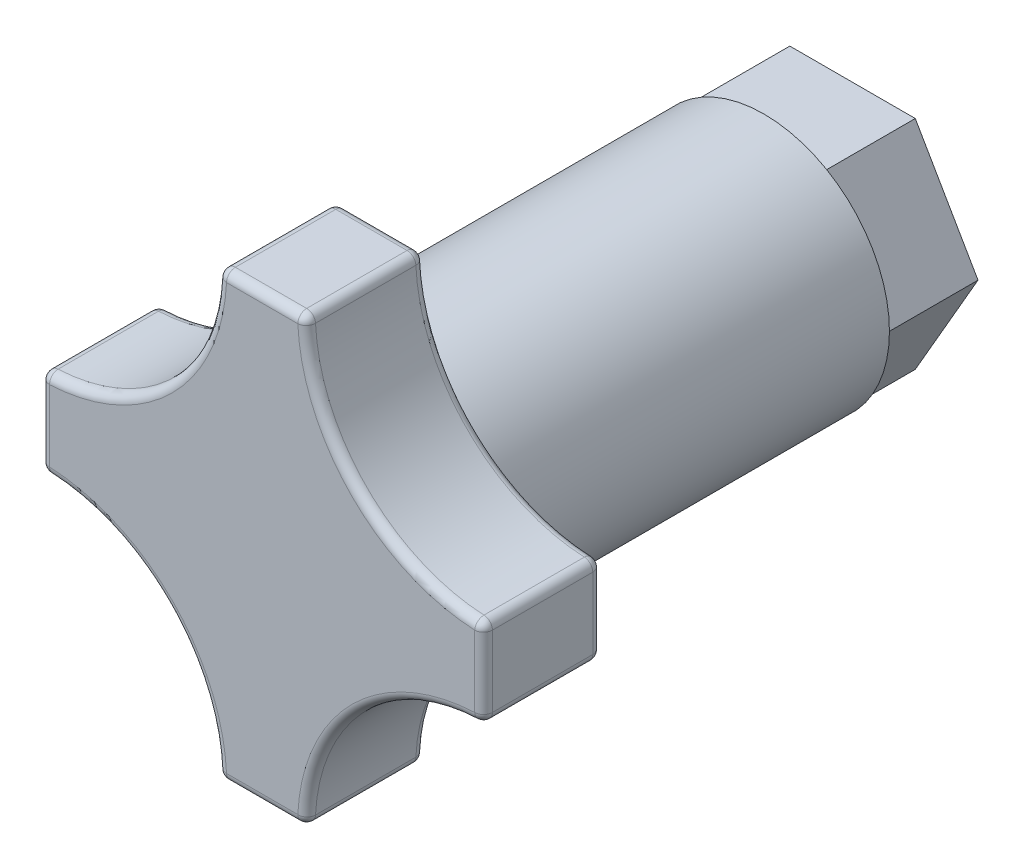
SolidWorks part; units mm, degrees
ref_plane "Front Plane" through (0, 0, 0) normal (0, 0, 1) x (1, 0, 0)
ref_plane "Top Plane" through (0, 0, 0) normal (0, 1, 0) x (1, 0, 0)
ref_plane "Right Plane" through (0, 0, 0) normal (1, 0, 0) x (0, 0, -1)
sketch "Sketch1" plane through (0, 0, 0) normal (0, 0, 1) x (1, 0, 0)
  circle A0 centre (0, 0) radius 8.5
  dimension "D1" = 17
extrude "Boss-Extrude1" add sketch "Sketch1" along normal blind 40
sketch "Sketch2" plane through (0, 0, 40) normal (0, 0, 1) x (1, 0, 0)
  line L1 (15, 3) -> (-15, 3)
  line L2 (15, 3) -> (15, -3)
  line L3 (15, -3) -> (-15, -3)
  line L4 (-15, 3) -> (-15, -3)
  line L5 (15, 3) -> (-15, -3) construction
  line L6 (15, -3) -> (-15, 3) construction
  line L7 (3, 15) -> (-3, 15)
  line L8 (3, 15) -> (3, -15)
  line L9 (3, -15) -> (-3, -15)
  line L10 (-3, 15) -> (-3, -15)
  line L11 (3, 15) -> (-3, -15) construction
  line L12 (3, -15) -> (-3, 15) construction
  circle A0 centre (0, 0) radius 15 construction
  arc A1 (-3, 15) -> (-15, 3) centre (-15, 15) cw
  arc A2 (3, 15) -> (15, 3) centre (15, 15) ccw
  arc A3 (15, -3) -> (3, -15) centre (15, -15) ccw
  arc A4 (-3, -15) -> (-15, -3) centre (-15, -15) ccw
  point P0 (0, 0)
  point P6 (0, 0)
  circle M8 centre (0, 0) radius 8.5
  dimension "D1" = 30
  dimension "D2" = 6
extrude "Boss-Extrude2" add sketch "Sketch2" against normal blind 8 contours L7 L10 L8 M8 | L10 L1 M8 | L10 A1 L1 M8 | L10 L1 L8 M8 | L1 L10 L3 L8 | L10 L1 L3 M8 | L1 L4 L3 M8 | A4 L10 L3 M8 | L10 L3 M8 | L3 L10 L8 M8 | L3 L8 M8 | L1 L8 L3 M8 | A3 L3 L8 M8 | L3 L2 L1 M8 | A2 L8 L1 M8 | L8 L1 M8 | L10 L9 L8 M8
sketch "Sketch3" plane through (0, 0, 0) normal (0, 0, -1) x (-1, 0, 0)
  line L1 (4.25, 7.3612) -> (-4.25, 7.3612)
  line L2 (-4.25, 7.3612) -> (-8.5, 0)
  line L3 (-8.5, 0) -> (-4.25, -7.3612)
  line L4 (-4.25, -7.3612) -> (4.25, -7.3612)
  line L5 (4.25, -7.3612) -> (8.5, 0)
  line L6 (8.5, 0) -> (4.25, 7.3612)
  circle A0 centre (0, 0) radius 7.3612 construction
  circle A1 centre (0, 0) radius 8.5 construction
  point P1 (0, 0)
  point P12 (0, 0)
  point P13 (0, 0)
extrude "Cut-Extrude1" cut sketch "Sketch3" against normal blind 6 flip side to cut
fillet "Fillet2" radius 0.6 24 edges at (0, -15, 32) (6.5147, -6.5147, 32) (3, -15, 36) (15, 0, 32) (15, -3, 36) (6.5147, 6.5147, 32) (15, 3, 36) (0, 15, 32) (3, 15, 36) (-15, 0, 32) (-15, 3, 36) (-6.5147, 6.5147, 32) (-3, 15, 36) (-3, -15, 36) (-6.5147, -6.5147, 32) (-15, -3, 36) (-15, 0, 40) (-6.5147, 6.5147, 40) (0, 15, 40) (6.5147, 6.5147, 40) (15, 0, 40) (6.5147, -6.5147, 40) (0, -15, 40) (-6.5147, -6.5147, 40)
